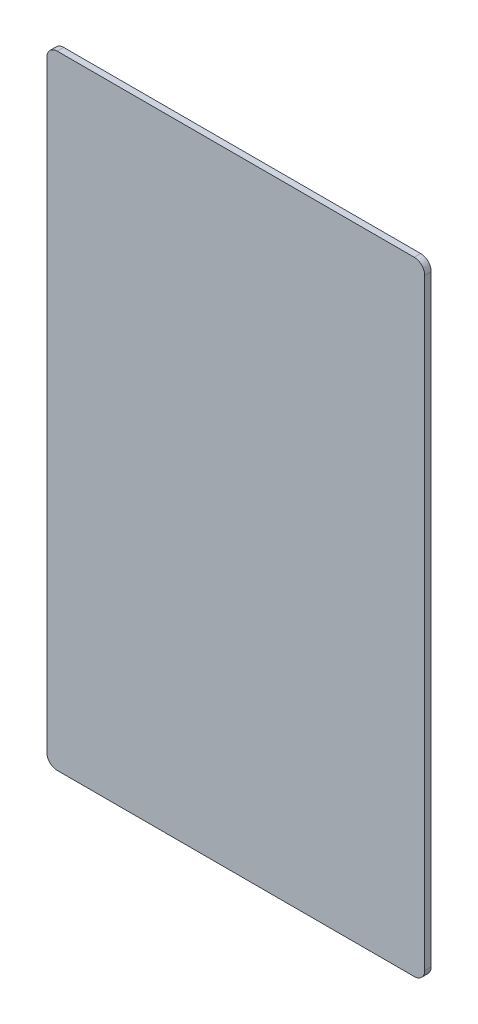
SolidWorks part; units mm, degrees
ref_plane "Front Plane" through (0, 0, 0) normal (0, 0, 1) x (1, 0, 0)
ref_plane "Top Plane" through (0, 0, 0) normal (0, 1, 0) x (1, 0, 0)
ref_plane "Right Plane" through (0, 0, 0) normal (1, 0, 0) x (0, 0, -1)
sketch "Sketch1" plane through (0, 0, 0) normal (0, 0, 1) x (1, 0, 0)
  line L1 (-51, 89) -> (51, 89)
  line L2 (-54, 86) -> (-54, -86)
  line L3 (-51, -89) -> (51, -89)
  line L4 (54, 86) -> (54, -86)
  line L5 (-54, 89) -> (54, -89) construction
  line L6 (-54, -89) -> (54, 89) construction
  arc A0 (-51, -89) -> (-54, -86) centre (-51, -86) cw
  arc A1 (51, -89) -> (54, -86) centre (51, -86) ccw
  arc A2 (54, 86) -> (51, 89) centre (51, 86) ccw
  arc A3 (-54, 86) -> (-51, 89) centre (-51, 86) cw
  point P0 (0, 0)
  dimension "D3" = 3
  dimension "D1" = 178
  dimension "D2" = 108
extrude "Boss-Extrude1" add sketch "Sketch1" along normal blind 1.85
sketch "Sketch2" plane through (0, 0, 1.85) normal (0, 0, 1) x (1, 0, 0)
  line L0 (-54, -82.2296) -> (-46, -82.2296) construction
  line L1 (-54, 86) -> (-54, -86) construction
  line L2 (-46, -89) -> (-46, -83) construction
  line L3 (-51, -89) -> (51, -89) construction
  line L5 (-46, -83) -> (49, -83)
  line L6 (-46, -83) -> (-46, 81)
  line L7 (-46, 81) -> (49, 81)
  line L8 (49, -83) -> (49, 81)
  dimension "D1" = 164
  dimension "D2" = 95
extrude "Boss-Extrude2" add sketch "Sketch2" against normal blind 5.75
